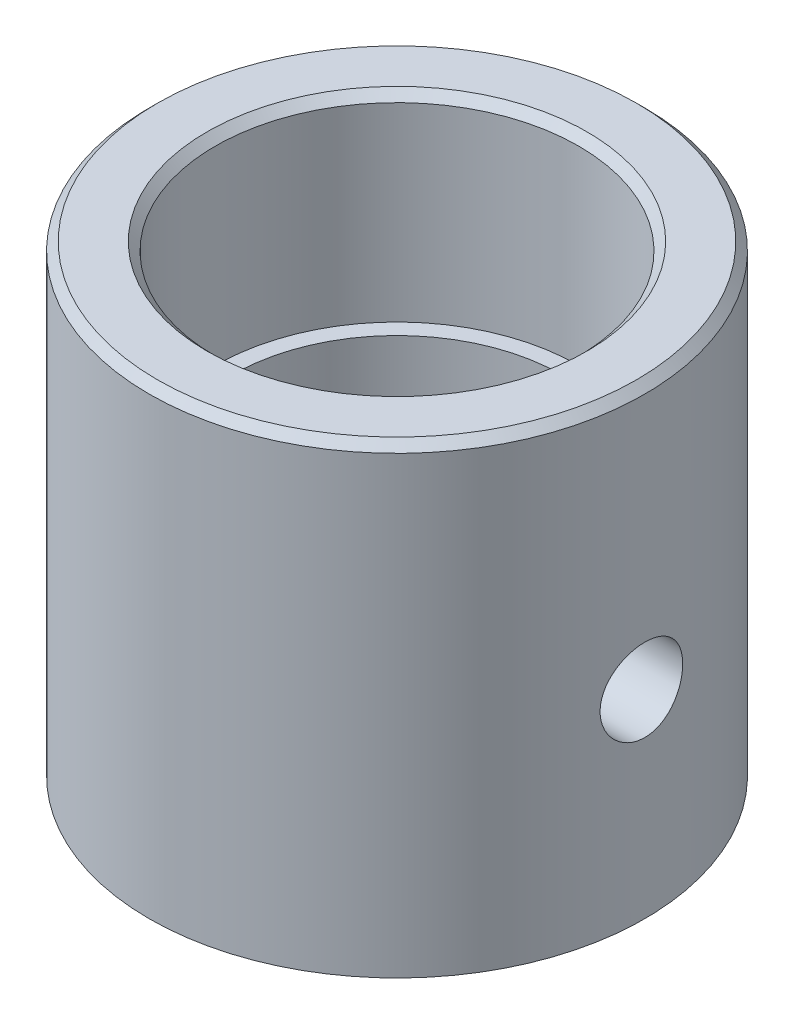
SolidWorks part; units mm, degrees
ref_plane "Front Plane" through (0, 0, 0) normal (0, 0, 1) x (1, 0, 0)
ref_plane "Top Plane" through (0, 0, 0) normal (0, 1, 0) x (1, 0, 0)
ref_plane "Right Plane" through (0, 0, 0) normal (1, 0, 0) x (0, 0, -1)
sketch "Sketch1" plane through (0, 0, 0) normal (0, 1, 0) x (1, 0, 0)
  circle A0 centre (0, 0) radius 15
  dimension "D1" = 30
extrude "Boss-Extrude1" add sketch "Sketch1" along normal blind 28
sketch "Sketch2" plane through (0, 28, 0) normal (0, 1, 0) x (1, 0, 0)
  circle A0 centre (0, 0) radius 10
  dimension "D1" = 20
extrude "Cut-Extrude1" cut sketch "Sketch2" against normal blind 27
sketch "Sketch3" plane through (0, 28, 0) normal (0, 1, 0) x (1, 0, 0)
  circle A0 centre (0, 0) radius 11
  dimension "D1" = 22
extrude "Cut-Extrude2" cut sketch "Sketch3" against normal blind 12
sketch "Sketch4" plane through (0, 0, 0) normal (1, 0, 0) x (0, 0, -1)
  line L0 (11, 28) -> (-11, 28) construction
  circle A0 centre (0, 12) radius 2.5
  dimension "D1" = 5
  dimension "D2" = 16
extrude "Cut-Extrude3" cut sketch "Sketch4" against normal through all both and the other way through all
chamfer "Chamfer1" distance 0.5 angle 45 2 edges at (0, 28, 11) (0, 28, 15)
